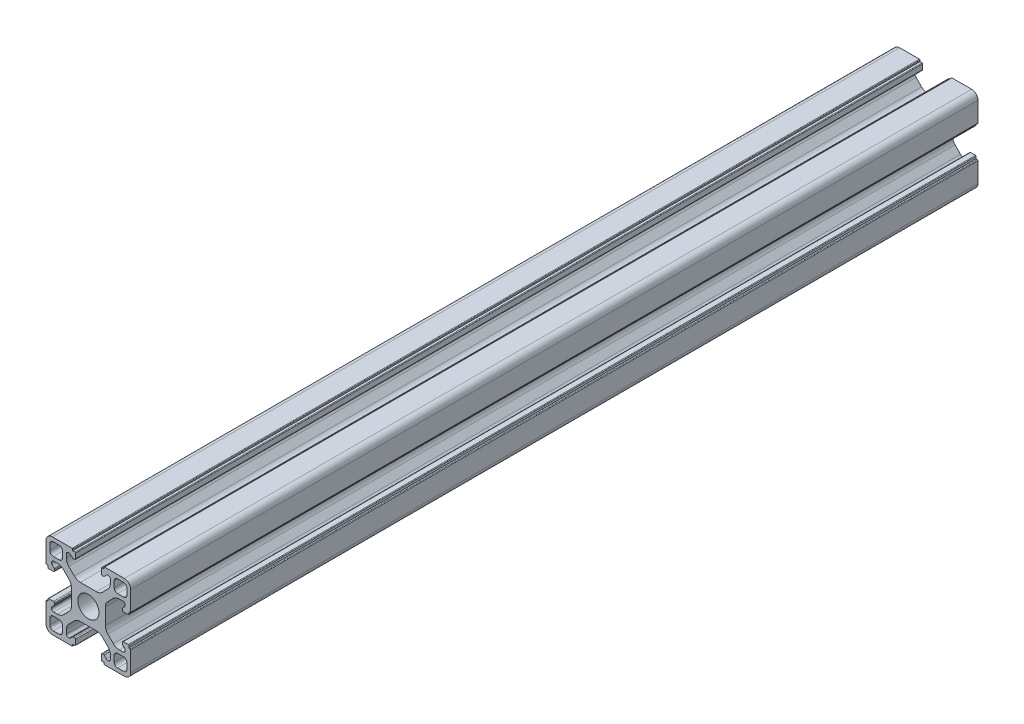
SolidWorks part; units mm, degrees
material "1060 Сплав"
ref_plane "Спереди" through (0, 0, 0) normal (0, 0, 1) x (1, 0, 0)
ref_plane "Сверху" through (0, 0, 0) normal (0, 1, 0) x (1, 0, 0)
ref_plane "Справа" through (0, 0, 0) normal (1, 0, 0) x (0, 0, -1)
sketch "Эскиз1" plane through (0, 0, 0) normal (0, 0, 1) x (1, 0, 0)
  line L0 (-22.0052, 70.3096) -> (-25.0052, 67.3096) construction
  line L1 (-31.1052, 65.2096) -> (-29.2064, 65.2096)
  line L2 (-31.1052, 61.2096) -> (-21.1052, 71.2096) construction
  line L3 (-23.5052, 68.8096) -> (-25.0052, 70.3096) construction
  line L4 (-27.7922, 65.7954) -> (-26.4909, 67.0967)
  line L5 (-24.2052, 67.3096) -> (-22.8052, 67.3096)
  line L6 (-25.0052, 68.1096) -> (-25.0052, 69.5096)
  line L7 (-22.8052, 70.3096) -> (-24.2052, 70.3096)
  line L8 (-25.9052, 69.4096) -> (-25.9052, 68.5109)
  line L9 (-27.3419, 69.2829) -> (-26.8616, 69.7632)
  line L10 (-27.9052, 70.7587) -> (-27.4052, 70.7587)
  line L11 (-27.5187, 69.2096) -> (-27.8052, 69.2096)
  line L12 (-26.508, 69.9096) -> (-26.4052, 69.9096)
  line L13 (-27.4052, 71.0596) -> (-27.4052, 70.7587)
  line L14 (-28.0552, 70.6087) -> (-28.0552, 69.4596)
  line L15 (-22.6052, 71.2096) -> (-27.2552, 71.2096)
  line L16 (-22.0052, 69.5096) -> (-22.0052, 68.1096)
  line L17 (-21.1052, 69.7096) -> (-21.1052, 65.0596)
  line L18 (-21.7061, 64.2596) -> (-22.8552, 64.2596)
  line L19 (-21.2552, 64.9096) -> (-21.5561, 64.9096)
  line L20 (-22.4052, 65.8068) -> (-22.4052, 65.9096)
  line L21 (-23.1052, 64.7961) -> (-23.1052, 64.5096)
  line L22 (-21.5561, 64.4096) -> (-21.5561, 64.9096)
  line L23 (-23.0319, 64.9729) -> (-22.5516, 65.4532)
  line L24 (-22.9052, 66.4096) -> (-23.8039, 66.4096)
  line L25 (-26.5194, 64.5226) -> (-25.2181, 65.8239)
  line L26 (-27.1052, 61.2096) -> (-27.1052, 63.1084)
  line L27 (-27.1052, 61.2096) -> (-27.1052, 59.3109)
  line L28 (-26.5194, 57.8967) -> (-25.2181, 56.5954)
  line L29 (-25.0052, 54.3096) -> (-25.0052, 52.9096)
  line L30 (-24.2052, 55.1096) -> (-22.8052, 55.1096)
  line L31 (-22.0052, 52.9096) -> (-22.0052, 54.3096)
  line L32 (-22.9052, 56.0096) -> (-23.8039, 56.0096)
  line L33 (-23.0319, 57.4464) -> (-22.5516, 56.9661)
  line L34 (-21.5561, 58.0096) -> (-21.5561, 57.5096)
  line L35 (-23.1052, 57.6232) -> (-23.1052, 57.9096)
  line L36 (-22.4052, 56.6125) -> (-22.4052, 56.5096)
  line L37 (-21.2552, 57.5096) -> (-21.5561, 57.5096)
  line L38 (-21.7061, 58.1596) -> (-22.8552, 58.1596)
  line L39 (-21.1052, 52.7096) -> (-21.1052, 57.3596)
  line L40 (-22.8052, 52.1096) -> (-24.2052, 52.1096)
  line L41 (-22.6052, 51.2096) -> (-27.2552, 51.2096)
  line L42 (-28.0552, 51.8106) -> (-28.0552, 52.9596)
  line L43 (-27.4052, 51.3596) -> (-27.4052, 51.6606)
  line L44 (-26.508, 52.5096) -> (-26.4052, 52.5096)
  line L45 (-27.5187, 53.2096) -> (-27.8052, 53.2096)
  line L46 (-27.9052, 51.6606) -> (-27.4052, 51.6606)
  line L47 (-27.3419, 53.1364) -> (-26.8616, 52.6561)
  line L48 (-25.9052, 53.0096) -> (-25.9052, 53.9084)
  line L49 (-27.7922, 56.6239) -> (-26.4909, 55.3226)
  line L50 (-31.1052, 57.2096) -> (-29.2064, 57.2096)
  line L51 (-22.0052, 52.1096) -> (-25.0052, 55.1096) construction
  line L52 (-31.1052, 61.2096) -> (-21.1052, 51.2096) construction
  line L53 (-23.5052, 53.6096) -> (-22.0052, 55.1096) construction
  line L54 (-31.1052, 57.2096) -> (-33.0039, 57.2096)
  line L55 (-34.4181, 56.6239) -> (-35.7194, 55.3226)
  line L56 (-38.0052, 55.1096) -> (-39.4052, 55.1096)
  line L57 (-37.2052, 54.3096) -> (-37.2052, 52.9096)
  line L58 (-39.4052, 52.1096) -> (-38.0052, 52.1096)
  line L59 (-36.3052, 53.0096) -> (-36.3052, 53.9084)
  line L60 (-34.8684, 53.1364) -> (-35.3487, 52.6561)
  line L61 (-34.3052, 51.6606) -> (-34.8052, 51.6606)
  line L62 (-34.6916, 53.2096) -> (-34.4052, 53.2096)
  line L63 (-35.7023, 52.5096) -> (-35.8052, 52.5096)
  line L64 (-34.8052, 51.3596) -> (-34.8052, 51.6606)
  line L65 (-34.1552, 51.8106) -> (-34.1552, 52.9596)
  line L66 (-39.6052, 51.2096) -> (-34.9552, 51.2096)
  line L67 (-40.2052, 52.9096) -> (-40.2052, 54.3096)
  line L68 (-41.1052, 52.7096) -> (-41.1052, 57.3596)
  line L69 (-40.5042, 58.1596) -> (-39.3552, 58.1596)
  line L70 (-40.9552, 57.5096) -> (-40.6542, 57.5096)
  line L71 (-39.8052, 56.6125) -> (-39.8052, 56.5096)
  line L72 (-39.1052, 57.6232) -> (-39.1052, 57.9096)
  line L73 (-40.6542, 58.0096) -> (-40.6542, 57.5096)
  line L74 (-39.1784, 57.4464) -> (-39.6587, 56.9661)
  line L75 (-39.3052, 56.0096) -> (-38.4064, 56.0096)
  line L76 (-35.6909, 57.8967) -> (-36.9922, 56.5954)
  line L77 (-35.1052, 61.2096) -> (-35.1052, 59.3109)
  line L78 (-40.2052, 52.1096) -> (-37.2052, 55.1096) construction
  line L79 (-31.1052, 61.2096) -> (-41.1052, 51.2096) construction
  line L80 (-38.7052, 53.6096) -> (-37.2052, 52.1096) construction
  line L81 (-35.1052, 61.2096) -> (-35.1052, 63.1084)
  line L82 (-35.6909, 64.5226) -> (-36.9922, 65.8239)
  line L83 (-37.2052, 68.1096) -> (-37.2052, 69.5096)
  line L84 (-38.0052, 67.3096) -> (-39.4052, 67.3096)
  line L85 (-40.2052, 69.5096) -> (-40.2052, 68.1096)
  line L86 (-39.3052, 66.4096) -> (-38.4064, 66.4096)
  line L87 (-39.1784, 64.9729) -> (-39.6587, 65.4532)
  line L88 (-40.6542, 64.4096) -> (-40.6542, 64.9096)
  line L89 (-39.1052, 64.7961) -> (-39.1052, 64.5096)
  line L90 (-39.8052, 65.8068) -> (-39.8052, 65.9096)
  line L91 (-40.9552, 64.9096) -> (-40.6542, 64.9096)
  line L92 (-40.5042, 64.2596) -> (-39.3552, 64.2596)
  line L93 (-41.1052, 69.7096) -> (-41.1052, 65.0596)
  line L94 (-39.4052, 70.3096) -> (-38.0052, 70.3096)
  line L95 (-39.6052, 71.2096) -> (-34.9552, 71.2096)
  line L96 (-34.1552, 70.6087) -> (-34.1552, 69.4596)
  line L97 (-34.8052, 71.0596) -> (-34.8052, 70.7587)
  line L98 (-35.7023, 69.9096) -> (-35.8052, 69.9096)
  line L99 (-34.6916, 69.2096) -> (-34.4052, 69.2096)
  line L100 (-34.3052, 70.7587) -> (-34.8052, 70.7587)
  line L101 (-34.8684, 69.2829) -> (-35.3487, 69.7632)
  line L102 (-36.3052, 69.4096) -> (-36.3052, 68.5109)
  line L103 (-34.4181, 65.7954) -> (-35.7194, 67.0967)
  line L104 (-31.1052, 65.2096) -> (-33.0039, 65.2096)
  line L105 (-42.8692, 61.2096) -> (-19.6008, 61.2096) construction
  line L106 (-40.2052, 70.3096) -> (-37.2052, 67.3096) construction
  line L107 (-31.1052, 49.1232) -> (-31.1052, 71.9286) construction
  line L108 (-31.1052, 61.2096) -> (-41.1052, 71.2096) construction
  line L109 (-38.7052, 68.8096) -> (-40.2052, 67.3096) construction
  arc A0 (-22.0052, 69.5096) -> (-22.8052, 70.3096) centre (-22.8052, 69.5096) ccw
  arc A1 (-24.2052, 70.3096) -> (-25.0052, 69.5096) centre (-24.2052, 69.5096) ccw
  arc A2 (-24.2052, 67.3096) -> (-25.0052, 68.1096) centre (-24.2052, 68.1096) cw
  arc A3 (-22.6052, 71.2096) -> (-21.1052, 69.7096) centre (-22.6052, 69.7096) cw
  arc A4 (-27.9052, 70.7587) -> (-28.0552, 70.6087) centre (-27.9052, 70.6087) ccw
  arc A5 (-27.2552, 71.2096) -> (-27.4052, 71.0596) centre (-27.2552, 71.0596) ccw
  arc A6 (-27.5187, 69.2096) -> (-27.3419, 69.2829) centre (-27.5187, 69.4596) ccw
  arc A7 (-27.8052, 69.2096) -> (-28.0552, 69.4596) centre (-27.8052, 69.4596) cw
  arc A8 (-26.8616, 69.7632) -> (-26.508, 69.9096) centre (-26.508, 69.4096) cw
  arc A9 (-26.4052, 69.9096) -> (-25.9052, 69.4096) centre (-26.4052, 69.4096) cw
  arc A10 (-28.6052, 61.2096) -> (-31.1052, 63.7096) centre (-31.1052, 61.2096) ccw
  arc A11 (-29.2064, 65.2096) -> (-27.7922, 65.7954) centre (-29.2064, 67.2096) ccw
  arc A12 (-25.9052, 68.5109) -> (-26.4909, 67.0967) centre (-27.9052, 68.5109) cw
  arc A13 (-22.0052, 68.1096) -> (-22.8052, 67.3096) centre (-22.8052, 68.1096) cw
  arc A14 (-22.4052, 65.9096) -> (-22.9052, 66.4096) centre (-22.9052, 65.9096) ccw
  arc A15 (-22.5516, 65.4532) -> (-22.4052, 65.8068) centre (-22.9052, 65.8068) ccw
  arc A16 (-23.1052, 64.5096) -> (-22.8552, 64.2596) centre (-22.8552, 64.5096) ccw
  arc A17 (-23.1052, 64.7961) -> (-23.0319, 64.9729) centre (-22.8552, 64.7961) cw
  arc A18 (-21.1052, 65.0596) -> (-21.2552, 64.9096) centre (-21.2552, 65.0596) cw
  arc A19 (-21.5561, 64.4096) -> (-21.7061, 64.2596) centre (-21.7061, 64.4096) cw
  arc A20 (-23.8039, 66.4096) -> (-25.2181, 65.8239) centre (-23.8039, 64.4096) ccw
  arc A21 (-27.1052, 63.1084) -> (-26.5194, 64.5226) centre (-25.1052, 63.1084) cw
  arc A22 (-22.8052, 52.1096) -> (-22.0052, 52.9096) centre (-22.8052, 52.9096) ccw
  arc A23 (-22.0052, 54.3096) -> (-22.8052, 55.1096) centre (-22.8052, 54.3096) ccw
  arc A24 (-25.0052, 54.3096) -> (-24.2052, 55.1096) centre (-24.2052, 54.3096) cw
  arc A25 (-21.1052, 52.7096) -> (-22.6052, 51.2096) centre (-22.6052, 52.7096) cw
  arc A26 (-21.5561, 58.0096) -> (-21.7061, 58.1596) centre (-21.7061, 58.0096) ccw
  arc A27 (-21.1052, 57.3596) -> (-21.2552, 57.5096) centre (-21.2552, 57.3596) ccw
  arc A28 (-23.1052, 57.6232) -> (-23.0319, 57.4464) centre (-22.8552, 57.6232) ccw
  arc A29 (-23.1052, 57.9096) -> (-22.8552, 58.1596) centre (-22.8552, 57.9096) cw
  arc A30 (-22.5516, 56.9661) -> (-22.4052, 56.6125) centre (-22.9052, 56.6125) cw
  arc A31 (-22.4052, 56.5096) -> (-22.9052, 56.0096) centre (-22.9052, 56.5096) cw
  arc A32 (-31.1052, 58.7096) -> (-28.6052, 61.2096) centre (-31.1052, 61.2096) ccw
  arc A33 (-27.1052, 59.3109) -> (-26.5194, 57.8967) centre (-25.1052, 59.3109) ccw
  arc A34 (-23.8039, 56.0096) -> (-25.2181, 56.5954) centre (-23.8039, 58.0096) cw
  arc A35 (-24.2052, 52.1096) -> (-25.0052, 52.9096) centre (-24.2052, 52.9096) cw
  arc A36 (-26.4052, 52.5096) -> (-25.9052, 53.0096) centre (-26.4052, 53.0096) ccw
  arc A37 (-26.8616, 52.6561) -> (-26.508, 52.5096) centre (-26.508, 53.0096) ccw
  arc A38 (-27.8052, 53.2096) -> (-28.0552, 52.9596) centre (-27.8052, 52.9596) ccw
  arc A39 (-27.5187, 53.2096) -> (-27.3419, 53.1364) centre (-27.5187, 52.9596) cw
  arc A40 (-27.2552, 51.2096) -> (-27.4052, 51.3596) centre (-27.2552, 51.3596) cw
  arc A41 (-27.9052, 51.6606) -> (-28.0552, 51.8106) centre (-27.9052, 51.8106) cw
  arc A42 (-25.9052, 53.9084) -> (-26.4909, 55.3226) centre (-27.9052, 53.9084) ccw
  arc A43 (-29.2064, 57.2096) -> (-27.7922, 56.6239) centre (-29.2064, 55.2096) cw
  arc A44 (-40.2052, 52.9096) -> (-39.4052, 52.1096) centre (-39.4052, 52.9096) ccw
  arc A45 (-38.0052, 52.1096) -> (-37.2052, 52.9096) centre (-38.0052, 52.9096) ccw
  arc A46 (-38.0052, 55.1096) -> (-37.2052, 54.3096) centre (-38.0052, 54.3096) cw
  arc A47 (-39.6052, 51.2096) -> (-41.1052, 52.7096) centre (-39.6052, 52.7096) cw
  arc A48 (-34.3052, 51.6606) -> (-34.1552, 51.8106) centre (-34.3052, 51.8106) ccw
  arc A49 (-34.9552, 51.2096) -> (-34.8052, 51.3596) centre (-34.9552, 51.3596) ccw
  arc A50 (-34.6916, 53.2096) -> (-34.8684, 53.1364) centre (-34.6916, 52.9596) ccw
  arc A51 (-34.4052, 53.2096) -> (-34.1552, 52.9596) centre (-34.4052, 52.9596) cw
  arc A52 (-35.3487, 52.6561) -> (-35.7023, 52.5096) centre (-35.7023, 53.0096) cw
  arc A53 (-35.8052, 52.5096) -> (-36.3052, 53.0096) centre (-35.8052, 53.0096) cw
  arc A54 (-33.6052, 61.2096) -> (-31.1052, 58.7096) centre (-31.1052, 61.2096) ccw
  arc A55 (-33.0039, 57.2096) -> (-34.4181, 56.6239) centre (-33.0039, 55.2096) ccw
  arc A56 (-36.3052, 53.9084) -> (-35.7194, 55.3226) centre (-34.3052, 53.9084) cw
  arc A57 (-40.2052, 54.3096) -> (-39.4052, 55.1096) centre (-39.4052, 54.3096) cw
  arc A58 (-39.8052, 56.5096) -> (-39.3052, 56.0096) centre (-39.3052, 56.5096) ccw
  arc A59 (-39.6587, 56.9661) -> (-39.8052, 56.6125) centre (-39.3052, 56.6125) ccw
  arc A60 (-39.1052, 57.9096) -> (-39.3552, 58.1596) centre (-39.3552, 57.9096) ccw
  arc A61 (-39.1052, 57.6232) -> (-39.1784, 57.4464) centre (-39.3552, 57.6232) cw
  arc A62 (-41.1052, 57.3596) -> (-40.9552, 57.5096) centre (-40.9552, 57.3596) cw
  arc A63 (-40.6542, 58.0096) -> (-40.5042, 58.1596) centre (-40.5042, 58.0096) cw
  arc A64 (-38.4064, 56.0096) -> (-36.9922, 56.5954) centre (-38.4064, 58.0096) ccw
  arc A65 (-35.1052, 59.3109) -> (-35.6909, 57.8967) centre (-37.1052, 59.3109) cw
  arc A66 (-39.4052, 70.3096) -> (-40.2052, 69.5096) centre (-39.4052, 69.5096) ccw
  arc A67 (-40.2052, 68.1096) -> (-39.4052, 67.3096) centre (-39.4052, 68.1096) ccw
  arc A68 (-37.2052, 68.1096) -> (-38.0052, 67.3096) centre (-38.0052, 68.1096) cw
  arc A69 (-41.1052, 69.7096) -> (-39.6052, 71.2096) centre (-39.6052, 69.7096) cw
  arc A70 (-40.6542, 64.4096) -> (-40.5042, 64.2596) centre (-40.5042, 64.4096) ccw
  arc A71 (-41.1052, 65.0596) -> (-40.9552, 64.9096) centre (-40.9552, 65.0596) ccw
  arc A72 (-39.1052, 64.7961) -> (-39.1784, 64.9729) centre (-39.3552, 64.7961) ccw
  arc A73 (-39.1052, 64.5096) -> (-39.3552, 64.2596) centre (-39.3552, 64.5096) cw
  arc A74 (-39.6587, 65.4532) -> (-39.8052, 65.8068) centre (-39.3052, 65.8068) cw
  arc A75 (-39.8052, 65.9096) -> (-39.3052, 66.4096) centre (-39.3052, 65.9096) cw
  arc A76 (-31.1052, 63.7096) -> (-33.6052, 61.2096) centre (-31.1052, 61.2096) ccw
  arc A77 (-35.1052, 63.1084) -> (-35.6909, 64.5226) centre (-37.1052, 63.1084) ccw
  arc A78 (-38.4064, 66.4096) -> (-36.9922, 65.8239) centre (-38.4064, 64.4096) cw
  arc A79 (-38.0052, 70.3096) -> (-37.2052, 69.5096) centre (-38.0052, 69.5096) cw
  arc A80 (-35.8052, 69.9096) -> (-36.3052, 69.4096) centre (-35.8052, 69.4096) ccw
  arc A81 (-35.3487, 69.7632) -> (-35.7023, 69.9096) centre (-35.7023, 69.4096) ccw
  arc A82 (-34.4052, 69.2096) -> (-34.1552, 69.4596) centre (-34.4052, 69.4596) ccw
  arc A83 (-34.6916, 69.2096) -> (-34.8684, 69.2829) centre (-34.6916, 69.4596) cw
  arc A84 (-34.9552, 71.2096) -> (-34.8052, 71.0596) centre (-34.9552, 71.0596) cw
  arc A85 (-34.3052, 70.7587) -> (-34.1552, 70.6087) centre (-34.3052, 70.6087) cw
  arc A86 (-36.3052, 68.5109) -> (-35.7194, 67.0967) centre (-34.3052, 68.5109) ccw
  arc A87 (-33.0039, 65.2096) -> (-34.4181, 65.7954) centre (-33.0039, 67.2096) cw
  point P0 (-31.1052, 61.2096)
  point P9 (-31.1052, 61.2096)
  point P40 (-22.4052, 64.9096)
  point P93 (-27.4052, 52.5096)
  point P144 (-27.4052, 69.9096)
  point P152 (-22.4052, 57.5096)
  point P153 (-31.1052, 57.2854)
  point P154 (-31.1052, 61.2096)
  point P189 (-39.8052, 57.5096)
  point P228 (-34.8052, 52.5096)
  point P229 (-35.0294, 61.2096)
  point P230 (-31.1052, 61.2096)
  point P268 (-34.8052, 69.9096)
  point P273 (-27.1809, 61.2096)
  point P306 (-39.8052, 64.9096)
  point P307 (-31.1052, 65.1339)
  point P309 (-31.1052, 61.2096)
  dimension "D3" = 5
  dimension "D6" = 2
  dimension "D1" = 2
  dimension "D2" = 6
  dimension "D4" = 4
  dimension "D5" = 0.9
extrude "Бобышка-Вытянуть1" add sketch "Эскиз1" along normal blind 200
